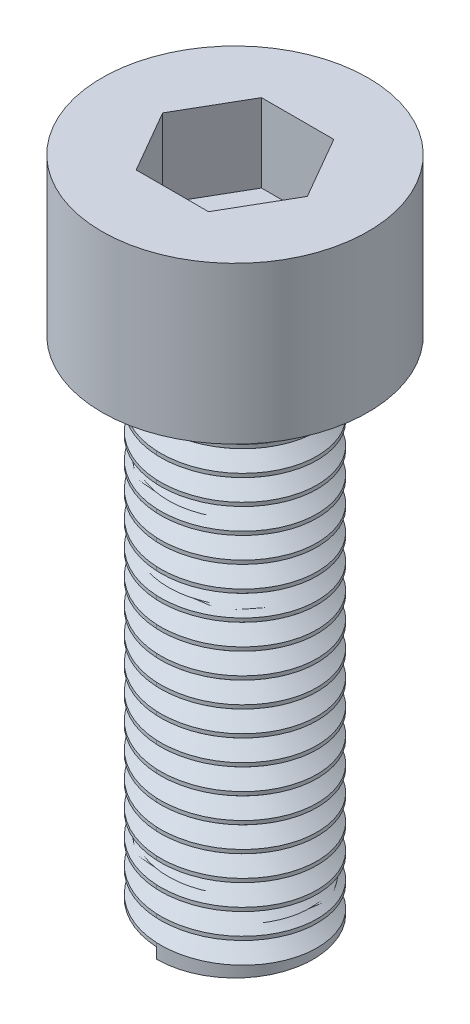
SolidWorks part; units mm, degrees
material "Acero aleado"
ref_plane "Alzado" through (0, 0, 0) normal (0, 0, 1) x (1, 0, 0)
ref_plane "Planta" through (0, 0, 0) normal (0, 1, 0) x (1, 0, 0)
ref_plane "Vista lateral" through (0, 0, 0) normal (1, 0, 0) x (0, 0, -1)
sketch "Sk_Cabeza" plane through (0, 0, 0) normal (0, 1, 0) x (1, 0, 0)
  circle A0 centre (0, 0) radius 4.25
  dimension "DIAM1" = 8.5
extrude "Cabeza" add sketch "Sk_Cabeza" along normal blind 5 from offset 0
sketch "Sk_Cana" plane through (0, 0, 0) normal (0, 1, 0) x (1, 0, 0)
  circle A0 centre (0, 0) radius 2.5
  dimension "DIAM2" = 5
extrude "Cana_rosca" add sketch "Sk_Cana" along normal blind 16 from offset 16
ref_plane "Plano_cabeza" through (0, 5, 0) normal (0, 1, 0) x (1, 0, 0)
sketch "Sk_Hueco_Allen" plane through (0, 5, 0) normal (0, 1, 0) x (1, 0, 0)
  line L0 (2.3094, 0) -> (1.1547, -2)
  line L1 (1.1547, -2) -> (-1.1547, -2)
  line L2 (-1.1547, -2) -> (-2.3094, 0)
  line L3 (-2.3094, 0) -> (-1.1547, 2)
  line L4 (-1.1547, 2) -> (1.1547, 2)
  line L5 (1.1547, 2) -> (2.3094, 0)
extrude "Hueco_Allen" cut sketch "Sk_Hueco_Allen" against normal blind 2.5
ref_plane "Plano_punta" through (0, -16, 0) normal (0, 1, 0) x (1, 0, 0)
sketch "Sk_Helice" plane through (0, -16, 0) normal (0, 1, 0) x (1, 0, 0)
  circle A0 centre (0, 0) radius 2.5
curve "Helice_rosca" pitch 0.8 height 15.4 turns 19.25
sketch "Sk_Perfil_rosca" plane through (0, 0, 0) normal (1, 0, 0) x (0, 0, -1)
  line L0 (-2.7, -16.48) -> (-2.0093, -16)
  line L1 (-2.0093, -16) -> (-2.7, -15.52)
  line L2 (-2.7, -15.52) -> (-2.7, -16.48)
sweep "Rosca_M5x0_8" cut profiles "Sk_Perfil_rosca" path "Helice_rosca"
